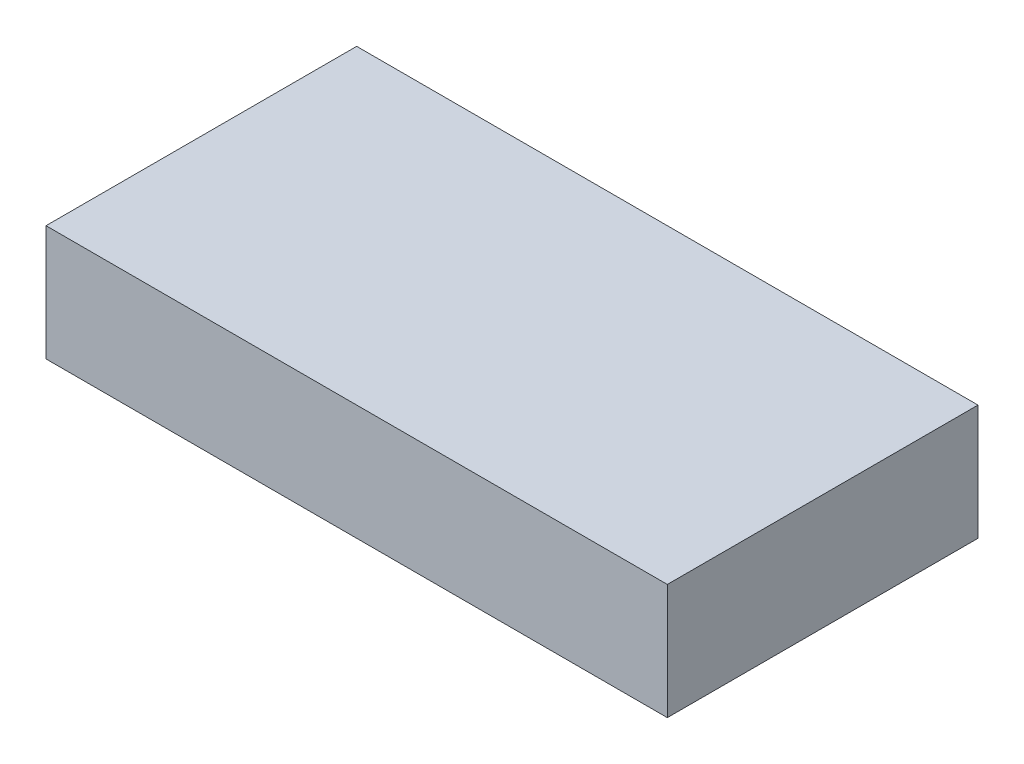
SolidWorks part; units mm, degrees
ref_plane "Front Plane" through (0, 0, 0) normal (0, 0, 1) x (1, 0, 0)
ref_plane "Top Plane" through (0, 0, 0) normal (0, 1, 0) x (1, 0, 0)
ref_plane "Right Plane" through (0, 0, 0) normal (1, 0, 0) x (0, 0, -1)
sketch "Sketch1" plane through (0, 0, 0) normal (0, 1, 0) x (1, 0, 0)
  line L1 (0, 0) -> (-70, 0)
  line L2 (0, 0) -> (0, -35)
  line L3 (0, -35) -> (-70, -35)
  line L4 (-70, 0) -> (-70, -35)
  dimension "D1" = 70
  dimension "D2" = 35
extrude "Boss-Extrude1" add sketch "Sketch1" along normal blind 13
equation "\"alto\"=1.3"
equation "\"D1@Boss-Extrude1\"=\"alto\""
equation "\"largo\"=7"
equation "\"D1@Sketch1\"=\"largo\""
equation "\"ancho\"=3.5"
equation "\"D2@Sketch1\"=\"ancho\""
